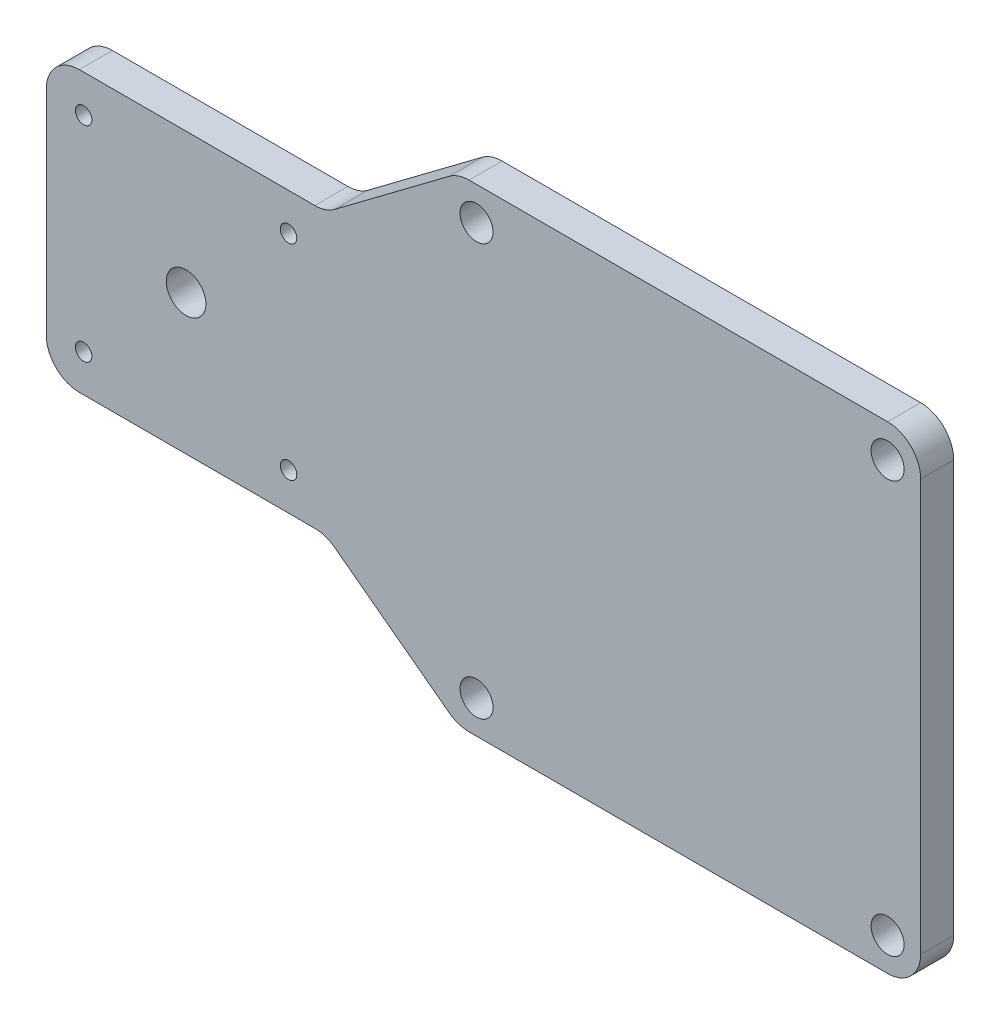
SolidWorks part; units mm, degrees
ref_plane "Front Plane" through (0, 0, 0) normal (0, 0, 1) x (1, 0, 0)
ref_plane "Top Plane" through (0, 0, 0) normal (0, 1, 0) x (1, 0, 0)
ref_plane "Right Plane" through (0, 0, 0) normal (1, 0, 0) x (0, 0, -1)
sketch "Sketch1" plane through (0, 0, 0) normal (0, 0, 1) x (1, 0, 0)
  line L0 (21.15, 21.15) -> (41.15, 36.15)
  line L1 (-21.15, -21.15) -> (21.15, -21.15)
  line L2 (-21.15, -21.15) -> (-21.15, 21.15)
  line L3 (-21.15, 21.15) -> (21.15, 21.15)
  line L5 (-21.15, -21.15) -> (21.15, 21.15) construction
  line L6 (-21.15, 21.15) -> (21.15, -21.15) construction
  line L7 (41.15, 36.15) -> (111.15, 36.15)
  line L9 (41.15, -36.15) -> (111.15, -36.15)
  line L10 (111.15, 36.15) -> (111.15, -36.15)
  line L11 (21.15, -21.15) -> (41.15, -36.15)
  point P0 (0, 0)
  dimension "D1" = 42.3
  dimension "D2" = 42.3
  dimension "D3" = 72.3
  dimension "D4" = 70
  dimension "D5" = 15
  dimension "D6" = 42.3
  dimension "D7" = 70
  dimension "D8" = 20
extrude "Boss-Extrude1" add sketch "Sketch1" along normal blind 5
fillet "Fillet2" radius 5 1 edges at (-21.15, -21.15, 2.5)
fillet "Fillet3" radius 5 1 edges at (-21.15, 21.15, 2.5)
fillet "Fillet4" radius 5 1 edges at (21.15, 21.15, 2.5)
fillet "Fillet5" radius 5 1 edges at (21.15, -21.15, 2.5)
fillet "Fillet6" radius 5 1 edges at (41.15, -36.15, 2.5)
fillet "Fillet7" radius 5 1 edges at (41.15, 36.15, 2.5)
fillet "Fillet8" radius 5 1 edges at (111.15, 36.15, 2.5)
fillet "Fillet9" radius 5 1 edges at (111.15, -36.15, 2.5)
sketch "Sketch2" plane through (0, 0, 5) normal (0, 0, 1) x (1, 0, 0)
  line L0 (-16.15, -21.15) -> (19.4833, -21.15) construction
  line L1 (-21.15, 16.15) -> (-21.15, -16.15) construction
  line L2 (19.4833, 21.15) -> (-16.15, 21.15) construction
  line L3 (106.15, 36.15) -> (42.8167, 36.15) construction
  line L8 (42.8167, -36.15) -> (106.15, -36.15) construction
  line L9 (111.15, -31.15) -> (111.15, 31.15) construction
  circle A0 centre (-15.5, -15.5) radius 1.25
  circle A1 centre (-15.5, 15.5) radius 1.25
  circle A2 centre (15.5, 15.5) radius 1.25
  circle A3 centre (15.5, -15.5) radius 1.25
  circle A4 centre (106.15, 31.15) radius 2.5
  circle A5 centre (106.15, -31.15) radius 2.5
  circle A6 centre (43.95, -31.15) radius 2.5
  circle A7 centre (43.95, 31.15) radius 2.5
  circle A10 centre (0, 0) radius 3
  dimension "D1" = 2.5
  dimension "D4" = 2.5
  dimension "D7" = 2.5
  dimension "D8" = 2.5
  dimension "D11" = 5
  dimension "D12" = 5
  dimension "D13" = 5
  dimension "D14" = 5
  dimension "D21" = 6
  dimension "D23" = 5
  dimension "D2" = 5.65
  dimension "D3" = 5.65
  dimension "D5" = 5.65
  dimension "D6" = 5.65
  dimension "D9" = 31
  dimension "D10" = 31
  dimension "D15" = 62.2
  dimension "D16" = 5
  dimension "D17" = 5
  dimension "D18" = 5
  dimension "D19" = 62.2
  dimension "D20" = 5
  dimension "D22" = 5
extrude "Cut-Extrude1" cut sketch "Sketch2" against normal blind 10
